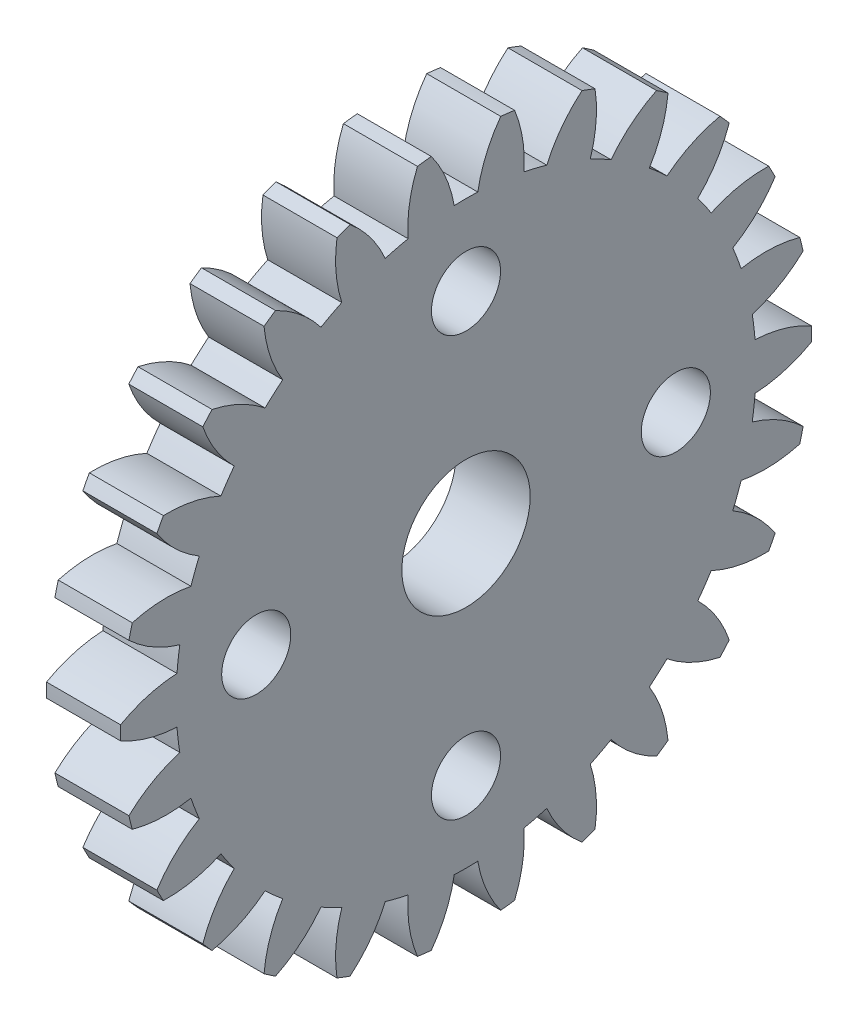
SolidWorks part; units mm, degrees
ref_plane "Plane1" through (0, 0, 0) normal (0, 0, 1) x (1, 0, 0)
ref_plane "Plane2" through (0, 0, 0) normal (0, 1, 0) x (1, 0, 0)
ref_plane "Plane3" through (0, 0, 0) normal (1, 0, 0) x (0, 0, -1)
sketch "HoldingSke" plane through (0, 0, 0) normal (0, 1, 0) x (1, 0, 0)
  line L0 (0, 0) -> (0.8988, -0.4384)
  line L1 (-15, 0) -> (100, 0) construction
  line L2 (0, 0) -> (-2.1039, 2.3779)
  line L3 (0, 0) -> (-11.863, 4.5341)
  line L4 (0, 0) -> (7.762, 3.7858)
  line L5 (0, 0) -> (-46.8476, -17.4728)
  line L6 (0, 0) -> (-4.1448, -2.7965)
  line L7 (-2.1039, 2.3779) -> (8.6586, 51.2059)
  line L8 (-76.2, 54.61) -> (-76.1, 54.61)
  line L9 (-71.009, 38.7566) -> (-53.1078, 45.2721)
  line L10 (-76.2, 71.12) -> (104.1128, 71.12)
  line L11 (0, 0) -> (-5, 0)
  line L12 (-76.2, 101.6) -> (-76.162, 101.6)
  line L13 (24.9733, 27.94) -> (52.9518, 28.4284)
  line L14 (24.9733, 27.94) -> (24.9743, 27.94)
  line L15 (24.9733, 27.94) -> (100.4006, 29.5858)
  line L16 (-63.627, -1) -> (-12.827, -1)
  circle A0 centre (0, 0) radius 0.4
  circle A1 centre (0, 0) radius 11.749
  circle A2 centre (0, 0) radius 37.5
  circle A3 centre (0, 0) radius 0.4
  dimension "MHD" = 23.498
  dimension "Hub_dia" = 75
  dimension "Bore" = 0.8
  dimension "MBD" = 0.8
  dimension "Num_teeth" = 26
  dimension "Pitch" = 1
  dimension "Overall_len" = 50
  dimension "Show_teeth" = 26
  dimension "Thickness" = 5
  dimension "OAL" = 50.0001
  dimension "T_dim" = 0.1
  dimension "Ap" = 20
  dimension "H" = 19.05
  dimension "Pitch_radius" = 180.3128
  dimension "Width" = 5
  dimension "Backlash" = 0.038
  dimension "Addendum_fac" = 1
  dimension "Dedendum_fac" = 1.25
  dimension "Clearance_fac" = 0.25
  dimension "Dedendum_add" = 0.001
  dimension "Module" = 1
sketch "BasProSke" plane through (0, 0, 0) normal (0, 1, 0) x (1, 0, 0)
  line L0 (-10, 0) -> (60, 0) construction
  line L1 (0, 0) -> (0, 14)
  line L2 (0, 0) -> (5, 0)
  line L3 (5, 0) -> (5, 14)
  line L4 (5, 14) -> (0, 14)
  dimension "Thickness" = 5
  dimension "Diameter" = 28
revolve "Base-Revolve" add sketch "BasProSke" angle 360 about L0
sketch "TooCutSke" plane through (0, 0, 0) normal (1, 0, 0) x (0, 0, -1)
  line L1 (0, 0) -> (0, 107) construction
  line L2 (0, 0) -> (-0.8514, 12.9721) construction
  line L3 (0, 0) -> (-3.1292, 25.771) construction
  line L4 (-0.8514, 12.9721) -> (-1.5646, 12.8855) construction
  arc A0 (0.477, 11.7393) -> (-0.477, 11.7393) centre (0, 0) ccw
  arc A1 (1.4241, 13.9529) -> (-1.4241, 13.9529) centre (0, 0) ccw
  circle A2 centre (0, 0) radius 13 construction
  circle A3 centre (0, 0) radius 12.216 construction
  arc A4 (-0.477, 11.7393) -> (-1.4241, 13.9529) centre (-5.6014, 10.8561) ccw
  arc A5 (1.4241, 13.9529) -> (0.477, 11.7393) centre (5.6014, 10.8561) ccw
  dimension "Root_dia" = 23.498
  dimension "Overcut_dia" = 28.0508
  dimension "Pitch_dia" = 26
  dimension "Base_dia" = 24.432
  dimension "Flank_rad" = 5.2
  dimension "Half_ang" = 6.923
  dimension "Half_CT" = 0.7184
extrude "ToothCut" cut sketch "TooCutSke" along normal through all
fillet "Breaks" [suppressed] radius 0.02
fillet "RootFillets" [suppressed] radius 0.251
pattern_circular "TeethCuts" count 26 every 13.846 about axis through (-10, 0, 0) along (1, 0, 0) of "ToothCut", "RootFillets", "Breaks"
sketch "HubNeaOneSke" plane through (0, 0, 0) normal (-1, 0, 0) x (0, 0, 1)
  circle A0 centre (0, 0) radius 11.749
  dimension "Diameter" = 23.498
extrude "HubNearOne" [suppressed] add sketch "HubNeaOneSke" along normal blind 45.0001
sketch "HubNeaBotSke" plane through (0, 0, 0) normal (-1, 0, 0) x (0, 0, 1)
  circle A0 centre (0, 0) radius 11.749
  dimension "Diameter" = 23.498
extrude "HubNearBoth" [suppressed] add sketch "HubNeaBotSke" along normal blind 22.5
ref_plane "FarPln" through (5, 0, 0) normal (1, 0, 0) x (0, 0, -1)
sketch "HubFarSke" plane through (5, 0, 0) normal (1, 0, 0) x (0, 0, -1)
  circle A0 centre (0, 0) radius 11.749
  dimension "Diameter" = 23.498
extrude "HubFar" [suppressed] add sketch "HubFarSke" along normal blind 22.5
sketch "BorSke" plane through (0, 0, 0) normal (1, 0, 0) x (0, 0, -1)
  circle A0 centre (0, 0) radius 0.4
  dimension "Diameter" = 0.8
extrude "Bore" cut sketch "BorSke" along normal mid plane 100.0001
sketch "KeySke" plane through (0, 0, 0) normal (1, 0, 0) x (0, 0, -1)
  line L0 (-0.05, 0) -> (-0.05, 0.5)
  line L1 (-0.05, 0.5) -> (0.05, 0.5)
  line L2 (0.05, 0.5) -> (0.05, 0)
  line L3 (0, 0) -> (0, 34) construction
  line L4 (-0.05, 0) -> (0.05, 0)
  dimension "Offset" = 0.5
  dimension "Width" = 0.1
extrude "Keyway" [suppressed] cut sketch "KeySke" along normal mid plane 100.0001
pattern_circular "Keyway2" [suppressed] count 2 every 90 about axis through (-10, 0, 0) along (1, 0, 0)
sketch "草图2" plane through (5, 0, 0) normal (1, 0, 0) x (0, 0, -1)
  circle A0 centre (0, 0) radius 2.6
extrude "切除-拉伸2" cut sketch "草图2" against normal blind 10
sketch "草图3" plane through (0, 0, 0) normal (-1, 0, 0) x (0, 0, 1)
  circle A1 centre (0, 8.5) radius 1.5
  circle A2 centre (-8.5, 0) radius 1.5
  circle A3 centre (0, -8.5) radius 1.5
  circle A4 centre (8.5, 0) radius 1.5
extrude "切除-拉伸3" cut sketch "草图3" against normal blind 10
sketch "草图4" plane through (0, 0, 0) normal (-1, 0, 0) x (0, 0, 1)
  circle A0 centre (0, 8.5) radius 1.5 construction
  circle A1 centre (0, 8.5) radius 1.5
  circle A2 centre (-8.5, 0) radius 1.5 construction
  circle A3 centre (-8.5, 0) radius 1.5
  circle A4 centre (8.5, 0) radius 1.5 construction
  circle A5 centre (8.5, 0) radius 1.5
  circle A6 centre (0, -8.5) radius 1.5 construction
  circle A7 centre (0, -8.5) radius 1.5
  circle A8 centre (0, 8.5) radius 1.3
  circle A9 centre (-8.5, 0) radius 1.3
  circle A10 centre (0, -8.5) radius 1.3
  circle A11 centre (8.5, 0) radius 1.3
extrude "凸台-拉伸1" add sketch "草图4" against normal up to surface (5 mm away) up to face at (5, 8.5, 1.5)
sketch "草图6" plane through (0, 0, 0) normal (-1, 0, 0) x (0, 0, 1)
  circle A0 centre (0, 0) radius 2.6 construction
  circle A1 centre (0, 0) radius 2.6
  circle A2 centre (8.5, 0) radius 1.3 construction
  circle A3 centre (8.5, 0) radius 1.3
  circle A4 centre (0, -8.5) radius 1.3 construction
  circle A5 centre (0, -8.5) radius 1.3
  circle A6 centre (-8.5, 0) radius 1.3 construction
  circle A7 centre (-8.5, 0) radius 1.3
  circle A8 centre (0, 8.5) radius 1.3 construction
  circle A9 centre (0, 8.5) radius 1.3
  arc A104 (11.7112, -0.9415) -> (13.9971, -0.2826) centre (11.4521, 4.252) ccw
  arc A105 (13.9971, -0.2826) -> (13.9971, 0.2826) centre (0, 0) ccw
  arc A106 (13.9971, 0.2826) -> (11.7112, 0.9415) centre (11.4521, -4.252) ccw
  arc A107 (11.7112, 0.9415) -> (11.5962, 1.8885) centre (0, 0) ccw
  arc A108 (11.5962, 1.8885) -> (13.6581, 3.0753) centre (10.1018, 6.8691) ccw
  arc A109 (13.6581, 3.0753) -> (13.5228, 3.6241) centre (0, 0) ccw
  arc A110 (13.5228, 3.6241) -> (11.1456, 3.7168) centre (12.1369, -1.3878) ccw
  arc A111 (11.1456, 3.7168) -> (10.8073, 4.6088) centre (0, 0) ccw
  arc A112 (10.8073, 4.6088) -> (12.5252, 6.2546) centre (8.1643, 9.087) ccw
  arc A113 (12.5252, 6.2546) -> (12.2625, 6.755) centre (0, 0) ccw
  arc A114 (12.2625, 6.755) -> (9.9322, 6.2762) centre (12.1164, 1.5571) ccw
  arc A115 (9.9322, 6.2762) -> (9.3903, 7.0612) centre (0, 0) ccw
  arc A116 (9.3903, 7.0612) -> (10.6644, 9.0703) centre (5.7524, 10.7768) ccw
  arc A117 (10.6644, 9.0703) -> (10.2896, 9.4934) centre (0, 0) ccw
  arc A118 (10.2896, 9.4934) -> (8.1416, 8.4707) centre (11.3916, 4.4115) ccw
  arc A119 (8.1416, 8.4707) -> (7.4276, 9.1033) centre (0, 0) ccw
  arc A120 (7.4276, 9.1033) -> (8.1839, 11.3589) centre (3.0062, 11.8403) ccw
  arc A121 (8.1839, 11.3589) -> (7.7187, 11.68) centre (0, 0) ccw
  arc A122 (7.7187, 11.68) -> (5.8779, 10.173) centre (10.0049, 7.0095) ccw
  arc A123 (5.8779, 10.173) -> (5.0332, 10.6163) centre (0, 0) ccw
  arc A124 (5.0332, 10.6163) -> (5.2277, 12.9873) centre (0.0853, 12.2157) ccw
  arc A125 (5.2277, 12.9873) -> (4.6992, 13.1878) centre (0, 0) ccw
  arc A126 (4.6992, 13.1878) -> (3.2725, 11.284) centre (8.0367, 9.2001) ccw
  arc A127 (3.2725, 11.284) -> (2.3463, 11.5123) centre (0, 0) ccw
  arc A128 (2.3463, 11.5123) -> (1.9677, 13.861) centre (-2.8406, 11.8811) ccw
  arc A129 (1.9677, 13.861) -> (1.4066, 13.9292) centre (0, 0) ccw
  arc A130 (1.4066, 13.9292) -> (0.477, 11.7393) centre (5.6014, 10.8561) ccw
  arc A131 (0.477, 11.7393) -> (-0.477, 11.7393) centre (0, 0) ccw
  arc A132 (-0.477, 11.7393) -> (-1.4066, 13.9292) centre (-5.6014, 10.8561) ccw
  arc A133 (-1.4066, 13.9292) -> (-1.9677, 13.861) centre (0, 0) ccw
  arc A134 (-1.9677, 13.861) -> (-2.3463, 11.5123) centre (2.8406, 11.8811) ccw
  arc A135 (-2.3463, 11.5123) -> (-3.2725, 11.284) centre (0, 0) ccw
  arc A136 (-3.2725, 11.284) -> (-4.6992, 13.1878) centre (-8.0367, 9.2001) ccw
  arc A137 (-4.6992, 13.1878) -> (-5.2277, 12.9873) centre (0, 0) ccw
  arc A138 (-5.2277, 12.9873) -> (-5.0332, 10.6163) centre (-0.0853, 12.2157) ccw
  arc A139 (-5.0332, 10.6163) -> (-5.8779, 10.173) centre (0, 0) ccw
  arc A140 (-5.8779, 10.173) -> (-7.7187, 11.68) centre (-10.0049, 7.0095) ccw
  arc A141 (-7.7187, 11.68) -> (-8.1839, 11.3589) centre (0, 0) ccw
  arc A142 (-8.1839, 11.3589) -> (-7.4276, 9.1033) centre (-3.0062, 11.8403) ccw
  arc A143 (-7.4276, 9.1033) -> (-8.1416, 8.4707) centre (0, 0) ccw
  arc A144 (-8.1416, 8.4707) -> (-10.2896, 9.4934) centre (-11.3916, 4.4115) ccw
  arc A145 (-10.2896, 9.4934) -> (-10.6644, 9.0703) centre (0, 0) ccw
  arc A146 (-10.6644, 9.0703) -> (-9.3903, 7.0612) centre (-5.7524, 10.7768) ccw
  arc A147 (-9.3903, 7.0612) -> (-9.9322, 6.2762) centre (0, 0) ccw
  arc A148 (-9.9322, 6.2762) -> (-12.2625, 6.755) centre (-12.1164, 1.5571) ccw
  arc A149 (-12.2625, 6.755) -> (-12.5252, 6.2546) centre (0, 0) ccw
  arc A150 (-12.5252, 6.2546) -> (-10.8073, 4.6088) centre (-8.1643, 9.087) ccw
  arc A151 (-10.8073, 4.6088) -> (-11.1456, 3.7168) centre (0, 0) ccw
  arc A152 (-11.1456, 3.7168) -> (-13.5228, 3.6241) centre (-12.1369, -1.3878) ccw
  arc A153 (-13.5228, 3.6241) -> (-13.6581, 3.0753) centre (0, 0) ccw
  arc A154 (-13.6581, 3.0753) -> (-11.5962, 1.8885) centre (-10.1018, 6.8691) ccw
  arc A155 (-11.5962, 1.8885) -> (-11.7112, 0.9415) centre (0, 0) ccw
  arc A156 (-11.7112, 0.9415) -> (-13.9971, 0.2826) centre (-11.4521, -4.252) ccw
  arc A157 (-13.9971, 0.2826) -> (-13.9971, -0.2826) centre (0, 0) ccw
  arc A158 (-13.9971, -0.2826) -> (-11.7112, -0.9415) centre (-11.4521, 4.252) ccw
  arc A159 (-11.7112, -0.9415) -> (-11.5962, -1.8885) centre (0, 0) ccw
  arc A160 (-11.5962, -1.8885) -> (-13.6581, -3.0753) centre (-10.1018, -6.8691) ccw
  arc A161 (-13.6581, -3.0753) -> (-13.5228, -3.6241) centre (0, 0) ccw
  arc A162 (-13.5228, -3.6241) -> (-11.1456, -3.7168) centre (-12.1369, 1.3878) ccw
  arc A163 (-11.1456, -3.7168) -> (-10.8073, -4.6088) centre (0, 0) ccw
  arc A164 (-10.8073, -4.6088) -> (-12.5252, -6.2546) centre (-8.1643, -9.087) ccw
  arc A165 (-12.5252, -6.2546) -> (-12.2625, -6.755) centre (0, 0) ccw
  arc A166 (-12.2625, -6.755) -> (-9.9322, -6.2762) centre (-12.1164, -1.5571) ccw
  arc A167 (-9.9322, -6.2762) -> (-9.3903, -7.0612) centre (0, 0) ccw
  arc A168 (-9.3903, -7.0612) -> (-10.6644, -9.0703) centre (-5.7524, -10.7768) ccw
  arc A169 (-10.6644, -9.0703) -> (-10.2896, -9.4934) centre (0, 0) ccw
  arc A170 (-10.2896, -9.4934) -> (-8.1416, -8.4707) centre (-11.3916, -4.4115) ccw
  arc A171 (-8.1416, -8.4707) -> (-7.4276, -9.1033) centre (0, 0) ccw
  arc A172 (-7.4276, -9.1033) -> (-8.1839, -11.3589) centre (-3.0062, -11.8403) ccw
  arc A173 (-8.1839, -11.3589) -> (-7.7187, -11.68) centre (0, 0) ccw
  arc A174 (-7.7187, -11.68) -> (-5.8779, -10.173) centre (-10.0049, -7.0095) ccw
  arc A175 (-5.8779, -10.173) -> (-5.0332, -10.6163) centre (0, 0) ccw
  arc A176 (-5.0332, -10.6163) -> (-5.2277, -12.9873) centre (-0.0853, -12.2157) ccw
  arc A177 (-5.2277, -12.9873) -> (-4.6992, -13.1878) centre (0, 0) ccw
  arc A178 (-4.6992, -13.1878) -> (-3.2725, -11.284) centre (-8.0367, -9.2001) ccw
  arc A179 (-3.2725, -11.284) -> (-2.3463, -11.5123) centre (0, 0) ccw
  arc A180 (-2.3463, -11.5123) -> (-1.9677, -13.861) centre (2.8406, -11.8811) ccw
  arc A181 (-1.9677, -13.861) -> (-1.4066, -13.9292) centre (0, 0) ccw
  arc A182 (-1.4066, -13.9292) -> (-0.477, -11.7393) centre (-5.6014, -10.8561) ccw
  arc A183 (-0.477, -11.7393) -> (0.477, -11.7393) centre (0, 0) ccw
  arc A184 (0.477, -11.7393) -> (1.4066, -13.9292) centre (5.6014, -10.8561) ccw
  arc A185 (1.4066, -13.9292) -> (1.9677, -13.861) centre (0, 0) ccw
  arc A186 (1.9677, -13.861) -> (2.3463, -11.5123) centre (-2.8406, -11.8811) ccw
  arc A187 (2.3463, -11.5123) -> (3.2725, -11.284) centre (0, 0) ccw
  arc A188 (3.2725, -11.284) -> (4.6992, -13.1878) centre (8.0367, -9.2001) ccw
  arc A189 (4.6992, -13.1878) -> (5.2277, -12.9873) centre (0, 0) ccw
  arc A190 (5.2277, -12.9873) -> (5.0332, -10.6163) centre (0.0853, -12.2157) ccw
  arc A191 (5.0332, -10.6163) -> (5.8779, -10.173) centre (0, 0) ccw
  arc A192 (5.8779, -10.173) -> (7.7187, -11.68) centre (10.0049, -7.0095) ccw
  arc A193 (7.7187, -11.68) -> (8.1839, -11.3589) centre (0, 0) ccw
  arc A194 (8.1839, -11.3589) -> (7.4276, -9.1033) centre (3.0062, -11.8403) ccw
  arc A195 (7.4276, -9.1033) -> (8.1416, -8.4707) centre (0, 0) ccw
  arc A196 (8.1416, -8.4707) -> (10.2896, -9.4934) centre (11.3916, -4.4115) ccw
  arc A197 (10.2896, -9.4934) -> (10.6644, -9.0703) centre (0, 0) ccw
  arc A198 (10.6644, -9.0703) -> (9.3903, -7.0612) centre (5.7524, -10.7768) ccw
  arc A199 (9.3903, -7.0612) -> (9.9322, -6.2762) centre (0, 0) ccw
  arc A200 (9.9322, -6.2762) -> (12.2625, -6.755) centre (12.1164, -1.5571) ccw
  arc A201 (12.2625, -6.755) -> (12.5252, -6.2546) centre (0, 0) ccw
  arc A202 (12.5252, -6.2546) -> (10.8073, -4.6088) centre (8.1643, -9.087) ccw
  arc A203 (10.8073, -4.6088) -> (11.1456, -3.7168) centre (0, 0) ccw
  arc A204 (11.1456, -3.7168) -> (13.5228, -3.6241) centre (12.1369, 1.3878) ccw
  arc A205 (13.5228, -3.6241) -> (13.6581, -3.0753) centre (0, 0) ccw
  arc A206 (13.6581, -3.0753) -> (11.5962, -1.8885) centre (10.1018, -6.8691) ccw
  arc A207 (11.5962, -1.8885) -> (11.7112, -0.9415) centre (0, 0) ccw
  arc A208 (11.7112, -0.9415) -> (13.9971, -0.2826) centre (11.4521, 4.252) ccw
  arc A209 (13.9971, -0.2826) -> (13.9971, 0.2826) centre (0, 0) ccw
  arc A210 (13.9971, 0.2826) -> (11.7112, 0.9415) centre (11.4521, -4.252) ccw
  arc A211 (11.7112, 0.9415) -> (11.5962, 1.8885) centre (0, 0) ccw
  arc A212 (11.5962, 1.8885) -> (13.6581, 3.0753) centre (10.1018, 6.8691) ccw
  arc A213 (13.6581, 3.0753) -> (13.5228, 3.6241) centre (0, 0) ccw
  arc A214 (13.5228, 3.6241) -> (11.1456, 3.7168) centre (12.1369, -1.3878) ccw
  arc A215 (11.1456, 3.7168) -> (10.8073, 4.6088) centre (0, 0) ccw
  arc A216 (10.8073, 4.6088) -> (12.5252, 6.2546) centre (8.1643, 9.087) ccw
  arc A217 (12.5252, 6.2546) -> (12.2625, 6.755) centre (0, 0) ccw
  arc A218 (12.2625, 6.755) -> (9.9322, 6.2762) centre (12.1164, 1.5571) ccw
  arc A219 (9.9322, 6.2762) -> (9.3903, 7.0612) centre (0, 0) ccw
  arc A220 (9.3903, 7.0612) -> (10.6644, 9.0703) centre (5.7524, 10.7768) ccw
  arc A221 (10.6644, 9.0703) -> (10.2896, 9.4934) centre (0, 0) ccw
  arc A222 (10.2896, 9.4934) -> (8.1416, 8.4707) centre (11.3916, 4.4115) ccw
  arc A223 (8.1416, 8.4707) -> (7.4276, 9.1033) centre (0, 0) ccw
  arc A224 (7.4276, 9.1033) -> (8.1839, 11.3589) centre (3.0062, 11.8403) ccw
  arc A225 (8.1839, 11.3589) -> (7.7187, 11.68) centre (0, 0) ccw
  arc A226 (7.7187, 11.68) -> (5.8779, 10.173) centre (10.0049, 7.0095) ccw
  arc A227 (5.8779, 10.173) -> (5.0332, 10.6163) centre (0, 0) ccw
  arc A228 (5.0332, 10.6163) -> (5.2277, 12.9873) centre (0.0853, 12.2157) ccw
  arc A229 (5.2277, 12.9873) -> (4.6992, 13.1878) centre (0, 0) ccw
  arc A230 (4.6992, 13.1878) -> (3.2725, 11.284) centre (8.0367, 9.2001) ccw
  arc A231 (3.2725, 11.284) -> (2.3463, 11.5123) centre (0, 0) ccw
  arc A232 (2.3463, 11.5123) -> (1.9677, 13.861) centre (-2.8406, 11.8811) ccw
  arc A233 (1.9677, 13.861) -> (1.4066, 13.9292) centre (0, 0) ccw
  arc A234 (1.4066, 13.9292) -> (0.477, 11.7393) centre (5.6014, 10.8561) ccw
  arc A235 (0.477, 11.7393) -> (-0.477, 11.7393) centre (0, 0) ccw
  arc A236 (-0.477, 11.7393) -> (-1.4066, 13.9292) centre (-5.6014, 10.8561) ccw
  arc A237 (-1.4066, 13.9292) -> (-1.9677, 13.861) centre (0, 0) ccw
  arc A238 (-1.9677, 13.861) -> (-2.3463, 11.5123) centre (2.8406, 11.8811) ccw
  arc A239 (-2.3463, 11.5123) -> (-3.2725, 11.284) centre (0, 0) ccw
  arc A240 (-3.2725, 11.284) -> (-4.6992, 13.1878) centre (-8.0367, 9.2001) ccw
  arc A241 (-4.6992, 13.1878) -> (-5.2277, 12.9873) centre (0, 0) ccw
  arc A242 (-5.2277, 12.9873) -> (-5.0332, 10.6163) centre (-0.0853, 12.2157) ccw
  arc A243 (-5.0332, 10.6163) -> (-5.8779, 10.173) centre (0, 0) ccw
  arc A244 (-5.8779, 10.173) -> (-7.7187, 11.68) centre (-10.0049, 7.0095) ccw
  arc A245 (-7.7187, 11.68) -> (-8.1839, 11.3589) centre (0, 0) ccw
  arc A246 (-8.1839, 11.3589) -> (-7.4276, 9.1033) centre (-3.0062, 11.8403) ccw
  arc A247 (-7.4276, 9.1033) -> (-8.1416, 8.4707) centre (0, 0) ccw
  arc A248 (-8.1416, 8.4707) -> (-10.2896, 9.4934) centre (-11.3916, 4.4115) ccw
  arc A249 (-10.2896, 9.4934) -> (-10.6644, 9.0703) centre (0, 0) ccw
  arc A250 (-10.6644, 9.0703) -> (-9.3903, 7.0612) centre (-5.7524, 10.7768) ccw
  arc A251 (-9.3903, 7.0612) -> (-9.9322, 6.2762) centre (0, 0) ccw
  arc A252 (-9.9322, 6.2762) -> (-12.2625, 6.755) centre (-12.1164, 1.5571) ccw
  arc A253 (-12.2625, 6.755) -> (-12.5252, 6.2546) centre (0, 0) ccw
  arc A254 (-12.5252, 6.2546) -> (-10.8073, 4.6088) centre (-8.1643, 9.087) ccw
  arc A255 (-10.8073, 4.6088) -> (-11.1456, 3.7168) centre (0, 0) ccw
  arc A256 (-11.1456, 3.7168) -> (-13.5228, 3.6241) centre (-12.1369, -1.3878) ccw
  arc A257 (-13.5228, 3.6241) -> (-13.6581, 3.0753) centre (0, 0) ccw
  arc A258 (-13.6581, 3.0753) -> (-11.5962, 1.8885) centre (-10.1018, 6.8691) ccw
  arc A259 (-11.5962, 1.8885) -> (-11.7112, 0.9415) centre (0, 0) ccw
  arc A260 (-11.7112, 0.9415) -> (-13.9971, 0.2826) centre (-11.4521, -4.252) ccw
  arc A261 (-13.9971, 0.2826) -> (-13.9971, -0.2826) centre (0, 0) ccw
  arc A262 (-13.9971, -0.2826) -> (-11.7112, -0.9415) centre (-11.4521, 4.252) ccw
  arc A263 (-11.7112, -0.9415) -> (-11.5962, -1.8885) centre (0, 0) ccw
  arc A264 (-11.5962, -1.8885) -> (-13.6581, -3.0753) centre (-10.1018, -6.8691) ccw
  arc A265 (-13.6581, -3.0753) -> (-13.5228, -3.6241) centre (0, 0) ccw
  arc A266 (-13.5228, -3.6241) -> (-11.1456, -3.7168) centre (-12.1369, 1.3878) ccw
  arc A267 (-11.1456, -3.7168) -> (-10.8073, -4.6088) centre (0, 0) ccw
  arc A268 (-10.8073, -4.6088) -> (-12.5252, -6.2546) centre (-8.1643, -9.087) ccw
  arc A269 (-12.5252, -6.2546) -> (-12.2625, -6.755) centre (0, 0) ccw
  arc A270 (-12.2625, -6.755) -> (-9.9322, -6.2762) centre (-12.1164, -1.5571) ccw
  arc A271 (-9.9322, -6.2762) -> (-9.3903, -7.0612) centre (0, 0) ccw
  arc A272 (-9.3903, -7.0612) -> (-10.6644, -9.0703) centre (-5.7524, -10.7768) ccw
  arc A273 (-10.6644, -9.0703) -> (-10.2896, -9.4934) centre (0, 0) ccw
  arc A274 (-10.2896, -9.4934) -> (-8.1416, -8.4707) centre (-11.3916, -4.4115) ccw
  arc A275 (-8.1416, -8.4707) -> (-7.4276, -9.1033) centre (0, 0) ccw
  arc A276 (-7.4276, -9.1033) -> (-8.1839, -11.3589) centre (-3.0062, -11.8403) ccw
  arc A277 (-8.1839, -11.3589) -> (-7.7187, -11.68) centre (0, 0) ccw
  arc A278 (-7.7187, -11.68) -> (-5.8779, -10.173) centre (-10.0049, -7.0095) ccw
  arc A279 (-5.8779, -10.173) -> (-5.0332, -10.6163) centre (0, 0) ccw
  arc A280 (-5.0332, -10.6163) -> (-5.2277, -12.9873) centre (-0.0853, -12.2157) ccw
  arc A281 (-5.2277, -12.9873) -> (-4.6992, -13.1878) centre (0, 0) ccw
  arc A282 (-4.6992, -13.1878) -> (-3.2725, -11.284) centre (-8.0367, -9.2001) ccw
  arc A283 (-3.2725, -11.284) -> (-2.3463, -11.5123) centre (0, 0) ccw
  arc A284 (-2.3463, -11.5123) -> (-1.9677, -13.861) centre (2.8406, -11.8811) ccw
  arc A285 (-1.9677, -13.861) -> (-1.4066, -13.9292) centre (0, 0) ccw
  arc A286 (-1.4066, -13.9292) -> (-0.477, -11.7393) centre (-5.6014, -10.8561) ccw
  arc A287 (-0.477, -11.7393) -> (0.477, -11.7393) centre (0, 0) ccw
  arc A288 (0.477, -11.7393) -> (1.4066, -13.9292) centre (5.6014, -10.8561) ccw
  arc A289 (1.4066, -13.9292) -> (1.9677, -13.861) centre (0, 0) ccw
  arc A290 (1.9677, -13.861) -> (2.3463, -11.5123) centre (-2.8406, -11.8811) ccw
  arc A291 (2.3463, -11.5123) -> (3.2725, -11.284) centre (0, 0) ccw
  arc A292 (3.2725, -11.284) -> (4.6992, -13.1878) centre (8.0367, -9.2001) ccw
  arc A293 (4.6992, -13.1878) -> (5.2277, -12.9873) centre (0, 0) ccw
  arc A294 (5.2277, -12.9873) -> (5.0332, -10.6163) centre (0.0853, -12.2157) ccw
  arc A295 (5.0332, -10.6163) -> (5.8779, -10.173) centre (0, 0) ccw
  arc A296 (5.8779, -10.173) -> (7.7187, -11.68) centre (10.0049, -7.0095) ccw
  arc A297 (7.7187, -11.68) -> (8.1839, -11.3589) centre (0, 0) ccw
  arc A298 (8.1839, -11.3589) -> (7.4276, -9.1033) centre (3.0062, -11.8403) ccw
  arc A299 (7.4276, -9.1033) -> (8.1416, -8.4707) centre (0, 0) ccw
  arc A300 (8.1416, -8.4707) -> (10.2896, -9.4934) centre (11.3916, -4.4115) ccw
  arc A301 (10.2896, -9.4934) -> (10.6644, -9.0703) centre (0, 0) ccw
  arc A302 (10.6644, -9.0703) -> (9.3903, -7.0612) centre (5.7524, -10.7768) ccw
  arc A303 (9.3903, -7.0612) -> (9.9322, -6.2762) centre (0, 0) ccw
  arc A304 (9.9322, -6.2762) -> (12.2625, -6.755) centre (12.1164, -1.5571) ccw
  arc A305 (12.2625, -6.755) -> (12.5252, -6.2546) centre (0, 0) ccw
  arc A306 (12.5252, -6.2546) -> (10.8073, -4.6088) centre (8.1643, -9.087) ccw
  arc A307 (10.8073, -4.6088) -> (11.1456, -3.7168) centre (0, 0) ccw
  arc A308 (11.1456, -3.7168) -> (13.5228, -3.6241) centre (12.1369, 1.3878) ccw
  arc A309 (13.5228, -3.6241) -> (13.6581, -3.0753) centre (0, 0) ccw
  arc A310 (13.6581, -3.0753) -> (11.5962, -1.8885) centre (10.1018, -6.8691) ccw
  arc A311 (11.5962, -1.8885) -> (11.7112, -0.9415) centre (0, 0) ccw
  dimension "D1" = 0
extrude "切除-拉伸4" cut sketch "草图6" against normal blind 2
sketch "草图7" plane through (2, 0, 0) normal (-1, 0, 0) x (0, 0, 1)
  circle A8 centre (-8.5, 0) radius 1.4
  circle A9 centre (0, 8.5) radius 1.4
  circle A10 centre (8.5, 0) radius 1.4
  circle A11 centre (0, -8.5) radius 1.4
extrude "切除-拉伸5" cut sketch "草图7" against normal blind 10
equation "' \"Module@HoldingSke\" = 6.35"
equation "' \"Num_teeth@HoldingSke\" = 12"
equation "' \"Ap@HoldingSke\" =  20"
equation "' \"Ap@HoldingSke\" = 20"
equation "' \"Width@HoldingSke\" = 0.5 * 25.4"
equation "' \"Hub_dia@HoldingSke\"= 1 * 25.4"
equation "' \"Hub_dia@HoldingSke\" = 1 * 25.4"
equation "' \"Overall_len@HoldingSke\" = 1.0 * 25.4"
equation "' \"Bore@HoldingSke\" = 0.75 * 25.4"
equation "' \"T_dim@HoldingSke\" = 0.1 * 25.4"
equation "' \"Width@KeySke\" = 0.25 * 25.4"
equation "' \"Show_teeth@HoldingSke\" = 13"
equation "' \"Backlash@HoldingSke\" = 0.009 * 25.4"
equation "' \"Addendum_fac@HoldingSke\" = 1.0"
equation "' \"Dedendum_fac@HoldingSke\" = 1.25"
equation "' \"Dedendum_add@HoldingSke\" = 0.00005 * 25.4"
equation "' \"Clearance_fac@HoldingSke\" = 0.25"
equation "\"Pitch@HoldingSke\" = 1 / \"Module@HoldingSke\""
equation "\"Overcut_dia@TooCutSke\" = (\"Num_teeth@HoldingSke\" + 2 * \"Addendum_fac@HoldingSke\") / \"Pitch@HoldingSke\" + 0.002 * 25.4"
equation "\"Pitch_dia@TooCutSke\" = \"Num_teeth@HoldingSke\" / \"Pitch@HoldingSke\""
equation "\"Base_dia@TooCutSke\" = \"Num_teeth@HoldingSke\" / \"Pitch@HoldingSke\" * cos((\"Ap@HoldingSke\"  * 3.14159265 / 180))"
equation "\"Root_dia@TooCutSke\" = (\"Num_teeth@HoldingSke\" + 2) / \"Pitch@HoldingSke\" - 2 * (\"Addendum_fac@HoldingSke\" + \"Dedendum_fac@HoldingSke\") / \"Pitch@HoldingSke\" - \"Dedendum_add@HoldingSke\" * 2"
equation "\"Half_ang@TooCutSke\" = 180 / \"Num_teeth@HoldingSke\""
equation "\"Half_CT@TooCutSke\" = \"Num_teeth@HoldingSke\" / \"Pitch@HoldingSke\" * sin((3.14159265 / 2 / \"Num_teeth@HoldingSke\")) / 2 - 7 * \"Backlash@HoldingSke\" / 4"
equation "\"Flank_rad@TooCutSke\" = \"Num_teeth@HoldingSke\" / \"Pitch@HoldingSke\" / 5"
equation "\"Radius@RootFillets\" = \"Clearance_fac@HoldingSke\" / \"Pitch@HoldingSke\" + \"Dedendum_add@HoldingSke\""
equation "\"Break_rad@Breaks\" = 0.02 / \"Pitch@HoldingSke\""
equation "\"Thickness@HoldingSke\" = \"Width@HoldingSke\""
equation "\"OAL@HoldingSke\" = \"Thickness@HoldingSke\""
equation "\"MHD@HoldingSke\" = (\"Num_teeth@HoldingSke\" + 2) / \"Pitch@HoldingSke\" - 2 * (\"Addendum_fac@HoldingSke\" + \"Dedendum_fac@HoldingSke\")  / \"Pitch@HoldingSke\" - \"Dedendum_add@HoldingSke\" * 2"
equation "\"MBD@HoldingSke\" = (\"Num_teeth@HoldingSke\" + 2) / \"Pitch@HoldingSke\" - 2 * (\"Addendum_fac@HoldingSke\" + \"Dedendum_fac@HoldingSke\")  / \"Pitch@HoldingSke\" - \"Dedendum_add@HoldingSke\" * 2 - 0.002 * 25.4"
equation "\"MHD@HoldingSke\" = ((sgn( \"MHD@HoldingSke\" - \"Hub_dia@HoldingSke\" )-1)*( \"MHD@HoldingSke\" - \"Hub_dia@HoldingSke\" ))/-2+ \"Hub_dia@HoldingSke\""
equation "\"MBD@HoldingSke\" = ((sgn( \"MBD@HoldingSke\" - \"Bore@HoldingSke\" )-1)*( \"MBD@HoldingSke\" - \"Bore@HoldingSke\" ))/-2+ \"Bore@HoldingSke\""
equation "\"OAL@HoldingSke\" = ((sgn( \"OAL@HoldingSke\" - \"Overall_len@HoldingSke\" )+1)*( \"OAL@HoldingSke\" - \"Overall_len@HoldingSke\" ))/2 + \"Overall_len@HoldingSke\" + 0.000002 * 25.4"
equation "\"Num_teeth@TeethCuts\" = int( \"Show_teeth@HoldingSke\" ) + 1"
equation "\"Num_teeth@TeethCuts\" = ((sgn( \"Num_teeth@TeethCuts\" - \"Num_teeth@HoldingSke\" )-1)*( \"Num_teeth@TeethCuts\" - \"Num_teeth@HoldingSke\" ))/-2+ \"Num_teeth@HoldingSke\""
equation "\"Num_teeth@TeethCuts\" = ((sgn( \"Num_teeth@TeethCuts\" - 2.0)+1)*( \"Num_teeth@TeethCuts\" - 2.0))/2 +2.0"
equation "\"Angle@TeethCuts\" = 360.0 / \"Num_teeth@HoldingSke\""
equation "\"Diameter@BasProSke\" = (\"Num_teeth@HoldingSke\" + 2 * \"Addendum_fac@HoldingSke\") / \"Pitch@HoldingSke\""
equation "\"Thickness@BasProSke\"  = \"Thickness@HoldingSke\""
equation "' \"Fillet_rad@BasProSke\" =  \"Thickness@HoldingSke\" * 0.05"
equation "' \"Fillet_rad@BasProSke\" = \"Thickness@HoldingSke\" * 0.05"
equation "\"MHD@HoldingSke\" = ((sgn( \"MHD@HoldingSke\" - \"Root_dia@TooCutSke\" )-1)*( \"MHD@HoldingSke\" - \"Root_dia@TooCutSke\" ))/-2+ \"Root_dia@TooCutSke\""
equation "\"Diameter@HubNeaOneSke\" = \"MHD@HoldingSke\""
equation "\"Length@HubNearOne\" = \"OAL@HoldingSke\" - \"Thickness@BasProSke\""
equation "\"Diameter@HubNeaBotSke\" = \"MHD@HoldingSke\""
equation "\"Length@HubNearBoth\" = ( \"OAL@HoldingSke\" - \"Thickness@BasProSke\" ) / 2.0"
equation "\"Thickness@FarPln\" = \"Thickness@BasProSke\""
equation "\"Diameter@HubFarSke\" = \"MHD@HoldingSke\""
equation "\"Length@HubFar\" = ( \"OAL@HoldingSke\" - \"Thickness@BasProSke\" ) / 2.0"
equation "\"Diameter@BorSke\" = \"MBD@HoldingSke\""
equation "\"D1@Bore\" = \"OAL@HoldingSke\" * 2.0"
equation "\"D1@Keyway\" = \"OAL@HoldingSke\" * 2.0"
equation "\"Offset@KeySke\" = \"T_dim@HoldingSke\" + \"MBD@HoldingSke\" / 2.0"
